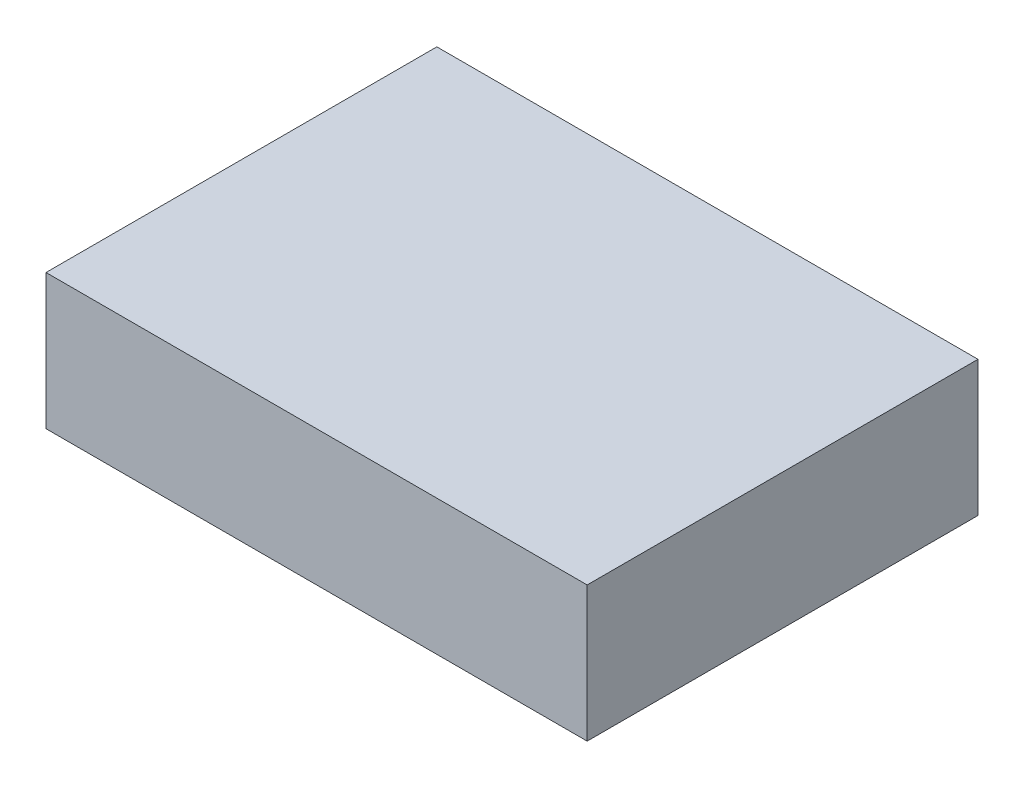
SolidWorks part; units mm, degrees
ref_plane "前视基准面" through (0, 0, 0) normal (0, 0, 1) x (1, 0, 0)
ref_plane "上视基准面" through (0, 0, 0) normal (0, 1, 0) x (1, 0, 0)
ref_plane "右视基准面" through (0, 0, 0) normal (1, 0, 0) x (0, 0, -1)
other "Configuration Table"
sketch "草图1" plane through (0, 0, 0) normal (0, 1, 0) x (1, 0, 0)
  line L1 (-18, 13) -> (18, 13)
  line L2 (-18, 13) -> (-18, -13)
  line L3 (-18, -13) -> (18, -13)
  line L4 (18, 13) -> (18, -13)
  line L5 (-18, 13) -> (18, -13) construction
  line L6 (-18, -13) -> (18, 13) construction
  point P0 (0, 0)
  dimension "D1" = 26
  dimension "D2" = 36
extrude "凸台-拉伸1" add sketch "草图1" along normal blind 9
